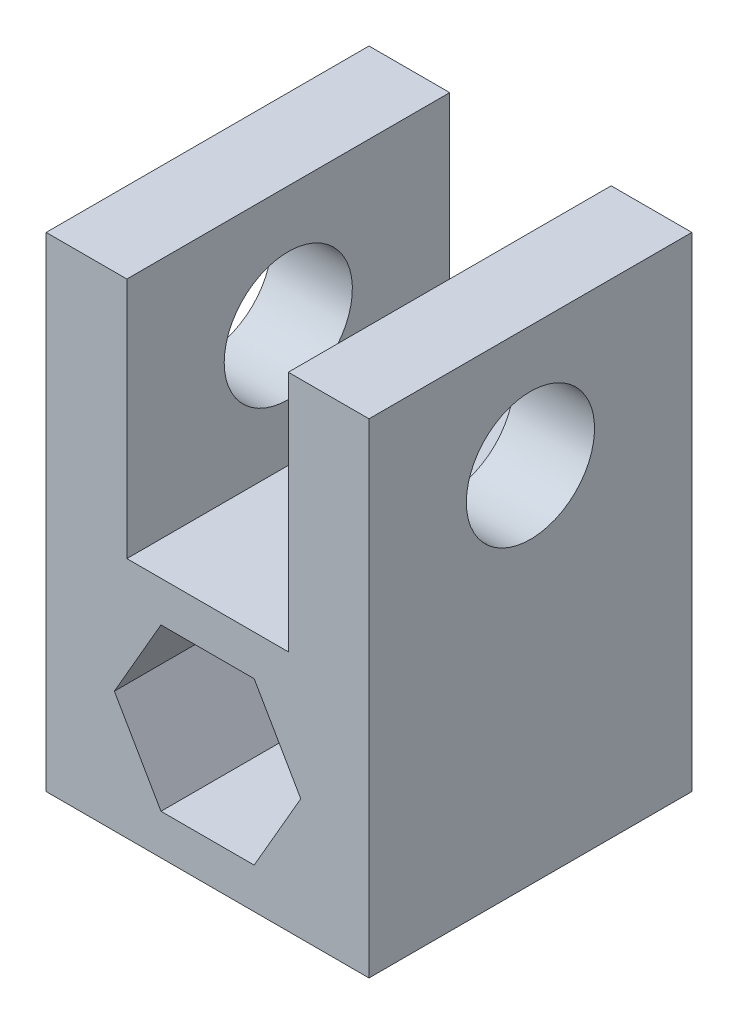
SolidWorks part; units mm, degrees
material "6061-T6 (SS)"
ref_plane "Front" through (0, 0, 0) normal (0, 0, 1) x (1, 0, 0)
ref_plane "Top" through (0, 0, 0) normal (0, 1, 0) x (1, 0, 0)
ref_plane "Right" through (0, 0, 0) normal (1, 0, 0) x (0, 0, -1)
sketch "Sketch1" plane through (0, 0, 0) normal (0, 0, 1) x (1, 0, 0)
  line L0 (-12.7, 0) -> (12.7, 0)
  line L1 (-12.7, 0) -> (-12.7, 38.1)
  line L2 (-12.7, 38.1) -> (-6.35, 38.1)
  line L3 (-6.35, 38.1) -> (-6.35, 19.05)
  line L4 (-6.35, 19.05) -> (6.35, 19.05)
  line L5 (6.35, 19.05) -> (6.35, 38.1)
  line L6 (6.35, 38.1) -> (12.7, 38.1)
  line L7 (12.7, 38.1) -> (12.7, 0)
  point P4 (0, 0)
  dimension "D1" = 25.4
  dimension "D2" = 38.1
  dimension "D3" = 6.35
  dimension "D4" = 19.05
extrude "Boss-Extrude1" add sketch "Sketch1" along normal blind 25.4
sketch "Sketch2" plane through (0, 0, 25.4) normal (0, 0, 1) x (1, 0, 0)
  line L0 (0, 0) -> (0, 3.175) construction
  line L1 (3.6662, 15.875) -> (-3.6662, 15.875)
  line L2 (-3.6662, 15.875) -> (-7.3323, 9.525)
  line L3 (-7.3323, 9.525) -> (-3.6662, 3.175)
  line L4 (-3.6662, 3.175) -> (3.6662, 3.175)
  line L5 (3.6662, 3.175) -> (7.3323, 9.525)
  line L6 (7.3323, 9.525) -> (3.6662, 15.875)
  line L7 (0, 15.875) -> (0, 19.05) construction
  line L8 (6.35, 19.05) -> (-6.35, 19.05) construction
  circle A0 centre (0, 9.525) radius 6.35 construction
  dimension "D1" = 12.7
extrude "Cut-Extrude1" cut sketch "Sketch2" against normal through all
sketch "Sketch6" plane through (-12.7, 0, 0) normal (-1, 0, 0) x (0, 0, 1)
  line L0 (25.4, 38.1) -> (0, 38.1) construction
  line L1 (25.4, 38.1) -> (25.4, 0) construction
  point P0 (12.7, 28.575)
  dimension "D1" = 9.525
  dimension "D2" = 12.7
hole_wizard "3/8 Clearance Hole1" positions "Sketch6" profile "Sketch4" hole size "3/8" standard "ANSI Inch" end condition through all
sketch "Sketch4" plane through (-12.7, 28.575, 12.7) normal (0, 1, 0) x (0, 0, 1)
  line L0 (0, 0) -> (0, 25.4)
  line L1 (0, 25.4) -> (5.0419, 25.4)
  line L2 (5.0419, 25.4) -> (5.0419, 0)
  line L5 (5.0419, 0) -> (0, 0)
  line L11 (0, -6.35) -> (0, 107.95) construction
  dimension "Thru Hole Dia." = 10.0838
  dimension "Thru Hole Depth" = 25.4
